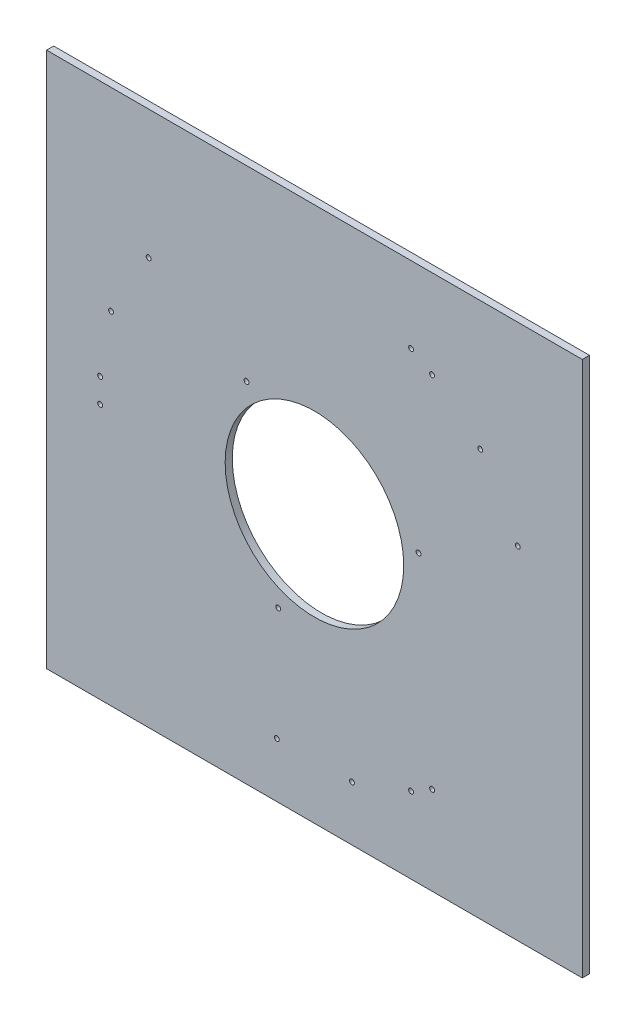
SolidWorks part; units mm, degrees
ref_plane "Piano frontale" through (0, 0, 0) normal (0, 0, 1) x (1, 0, 0)
ref_plane "Piano superiore" through (0, 0, 0) normal (0, 1, 0) x (1, 0, 0)
ref_plane "Piano destro" through (0, 0, 0) normal (1, 0, 0) x (0, 0, -1)
sketch "Schizzo1" plane through (0, 0, 0) normal (0, 0, 1) x (1, 0, 0)
  line L1 (187.5, 187.5) -> (-187.5, 187.5)
  line L2 (187.5, 187.5) -> (187.5, -187.5)
  line L3 (187.5, -187.5) -> (-187.5, -187.5)
  line L4 (-187.5, 187.5) -> (-187.5, -187.5)
  line L5 (187.5, 187.5) -> (-187.5, -187.5) construction
  line L6 (187.5, -187.5) -> (-187.5, 187.5) construction
  point P0 (0, 0)
  dimension "D1" = 375
  dimension "D2" = 375
extrude "Estrusione-Estrusione1" add sketch "Schizzo1" along normal blind 5
sketch "Schizzo2" plane through (0, 0, 5) normal (0, 0, 1) x (1, 0, 0)
  circle A0 centre (0, 0) radius 62.5
  dimension "D1" = 125
extrude "Taglio-Estrusione1" cut sketch "Schizzo2" against normal up to next
sketch "Schizzo4" plane through (0, 0, 5) normal (0, 0, 1) x (1, 0, 0)
  line L0 (0, 0) -> (0, -152.5) construction
  line L1 (0, 0) -> (-26.3077, -149.1984) construction
  line L2 (0, 0) -> (26.3077, -149.1984) construction
  dimension "D1" = 10
  dimension "D2" = 10
  dimension "D3" = 151.5
hole_wizard "Foro per Vite M3-4" positions "Schizzo5" profile "Schizzo6" hole size "M3" standard "ISO" end condition up to next
sketch "Schizzo5" plane through (0, 0, 5) normal (0, 0, 1) x (1, 0, 0)
  point P3 (-26.3077, -149.1984)
  point P5 (26.3077, -149.1984)
sketch "Schizzo6" plane through (-26.3077, -149.1984, 5) normal (1, 0, 0) x (0, -1, 0)
  line L0 (0, 0) -> (0, 5)
  line L1 (0, 5) -> (1.7, 5)
  line L2 (1.7, 5) -> (1.7, 0)
  line L5 (1.7, 0) -> (0, 0)
  line L11 (0, -6.35) -> (0, 107.95) construction
  dimension "Thru Hole Dia." = 3.4
  dimension "Thru Hole Depth" = 5
pattern_circular "RipetizioneCircolare1" count 3 over 360 about axis through (0, 0, 0) along (0, 0, 1) of "Foro per Vite M3-4"
sketch "Schizzo11" plane through (0, 0, 5) normal (0, 0, 1) x (1, 0, 0)
  line L0 (0, 0) -> (-25.3095, -69.5373) construction
  line L1 (0, 0) -> (0, -37.6692) construction
  circle A0 centre (0, 0) radius 74 construction
  dimension "D1" = 148
  dimension "D2" = 20
hole_wizard "Foro per Vite M3-2" positions "Schizzo12" profile "Schizzo13" hole size "M3" standard "ISO" end condition up to next
sketch "Schizzo12" plane through (0, 0, 5) normal (0, 0, 1) x (1, 0, 0)
  point P0 (-25.3095, -69.5373)
sketch "Schizzo13" plane through (-25.3095, -69.5373, 5) normal (1, 0, 0) x (0, -1, 0)
  line L0 (0, 0) -> (0, 5)
  line L1 (0, 5) -> (1.7, 5)
  line L2 (1.7, 5) -> (1.7, 0)
  line L5 (1.7, 0) -> (0, 0)
  line L11 (0, -6.35) -> (0, 107.95) construction
  dimension "Thru Hole Dia." = 3.4
  dimension "Thru Hole Depth" = 5
pattern_circular "RipetizioneCircolare3" count 3 over 360 about axis through (0, 0, 0) along (0, 0, 1) of "Foro per Vite M3-2"
sketch "Schizzo20" plane through (0, 0, 5) normal (0, 0, 1) x (1, 0, 0)
  line L0 (75, 129.9038) -> (67.6388, 134.1538) construction
  line L1 (82.3612, 125.6538) -> (75, 129.9038) construction
  line L2 (75, 129.9038) -> (0, 0) construction
  line L3 (0, 0) -> (0, 31.4624) construction
  dimension "D1" = 150
  dimension "D2" = 8.5
  dimension "D3" = 30
hole_wizard "Foro per Vite M3-5" positions "Schizzo21" profile "Schizzo22" hole size "M3" standard "ISO" end condition up to next
sketch "Schizzo21" plane through (0, 0, 5) normal (0, 0, 1) x (1, 0, 0)
  point P0 (67.6388, 134.1538)
  point P3 (82.3612, 125.6538)
sketch "Schizzo22" plane through (67.6388, 134.1538, 5) normal (1, 0, 0) x (0, -1, 0)
  line L0 (0, 0) -> (0, 5)
  line L1 (0, 5) -> (1.7, 5)
  line L2 (1.7, 5) -> (1.7, 0)
  line L5 (1.7, 0) -> (0, 0)
  line L11 (0, -6.35) -> (0, 107.95) construction
  dimension "Thru Hole Dia." = 3.4
  dimension "Thru Hole Depth" = 5
pattern_circular "RipetizioneCircolare4" count 3 over 360 about axis through (0, 0, 0) along (0, 0, 1) of "Foro per Vite M3-5"
